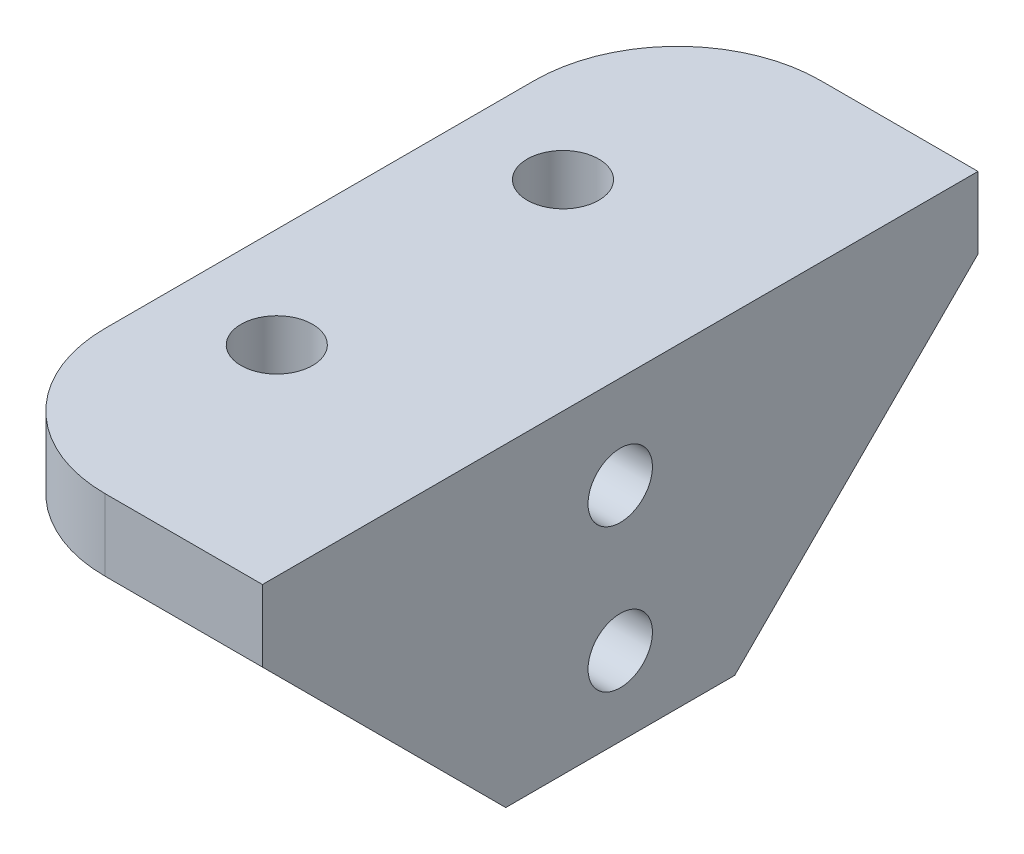
SolidWorks part; units mm, degrees
ref_plane "Plano frontal" through (0, 0, 0) normal (0, 0, 1) x (1, 0, 0)
ref_plane "Plano superior" through (0, 0, 0) normal (0, 1, 0) x (1, 0, 0)
ref_plane "Plano direito" through (0, 0, 0) normal (1, 0, 0) x (0, 0, -1)
sketch "Esboço1" plane through (0, 0, 0) normal (0, 1, 0) x (1, 0, 0)
  line L1 (0, 0) -> (15, 0)
  line L2 (0, 0) -> (0, 50)
  line L3 (0, 50) -> (15, 50)
  line L4 (15, 0) -> (15, 50)
  dimension "D1" = 50
  dimension "D2" = 15
extrude "Ressalto-extrusão1" add sketch "Esboço1" along normal blind 5
sketch "Esboço2" plane through (0, 5, 0) normal (0, 1, 0) x (1, 0, 0)
  line L0 (0, 25) -> (15, 25) construction
  line L1 (0, 50) -> (0, 0) construction
  line L2 (15, 0) -> (15, 50) construction
  line L3 (7, 50) -> (7, 0) construction
  line L6 (15, 50) -> (0, 50) construction
  line L7 (0, 0) -> (15, 0) construction
  circle A0 centre (7, 35) radius 2.5
  circle A1 centre (7, 15) radius 2.5
  point P16 (0, 0)
  point P17 (0, 0)
  dimension "D3" = 5
  dimension "D1" = 10
  dimension "D2" = 10
  dimension "D4" = 8
extrude "Corte-extrusão1" cut sketch "Esboço2" against normal through all
fillet "Filete1" radius 10 2 edges at (0, 2.5, 0) (0, 2.5, -50)
sketch "Esboço3" plane through (15, 0, 0) normal (1, 0, 0) x (0, 0, -1)
  line L6 (25, 5) -> (25, -17) construction
  line L7 (0, 5) -> (50, 5) construction
  line L8 (50, 5) -> (0, 5)
  line L9 (0, 5) -> (0, 0)
  line L10 (0, 0) -> (17, -17)
  line L11 (17, -17) -> (33, -17)
  line L12 (50, 0) -> (33, -17)
  line L13 (50, 5) -> (50, 0)
  dimension "D1" = 22
  dimension "D2" = 8
extrude "Ressalto-extrusão2" add sketch "Esboço3" along normal blind 6
hole_wizard "Rebaixo para parafuso com cabeça redonda de M41" positions "Esboço5" profile "Esboço6" counterbore size "M4" standard "ISO" end condition through all
sketch "Esboço5" plane through (15, 0, 0) normal (-1, 0, 0) x (0, 0, 1)
  line L0 (-17, -17) -> (-33, -17) construction
  line L1 (-25, -17) -> (-25, 5) construction
  line L2 (-40, 5) -> (-10, 5) construction
  point P0 (-25, -11.5)
  point P2 (-25, -1.5)
  point P13 (0, 0)
  point P14 (0, 0)
  dimension "D1" = 5.5
  dimension "D2" = 10
sketch "Esboço6" plane through (15, -11.5, -25) normal (0, 1, 0) x (0, 0, 1)
  line L0 (0, 0) -> (0, 6)
  line L1 (0, 6) -> (2.25, 6)
  line L3 (2.25, 6) -> (2.25, 2.6)
  line L4 (4, 2.6) -> (2.25, 2.6)
  line L5 (4, 2.6) -> (4, 0.025)
  line L6 (4, 0.025) -> (4.025, 0)
  line L7 (4.025, 0) -> (0, 0)
  line L8 (-4, 0.025) -> (-4.025, 0) construction
  line L11 (0, -6.35) -> (0, 107.95) construction
  dimension "Thru Hole Dia." = 4.5
  dimension "Thru Hole Depth" = 6
  dimension "C'Bore Dia." = 8
  dimension "C'Bore Depth" = 2.6
  dimension "Near C'Sink Dia." = 8.05
  dimension "Near C'Sink Angle" = 90
